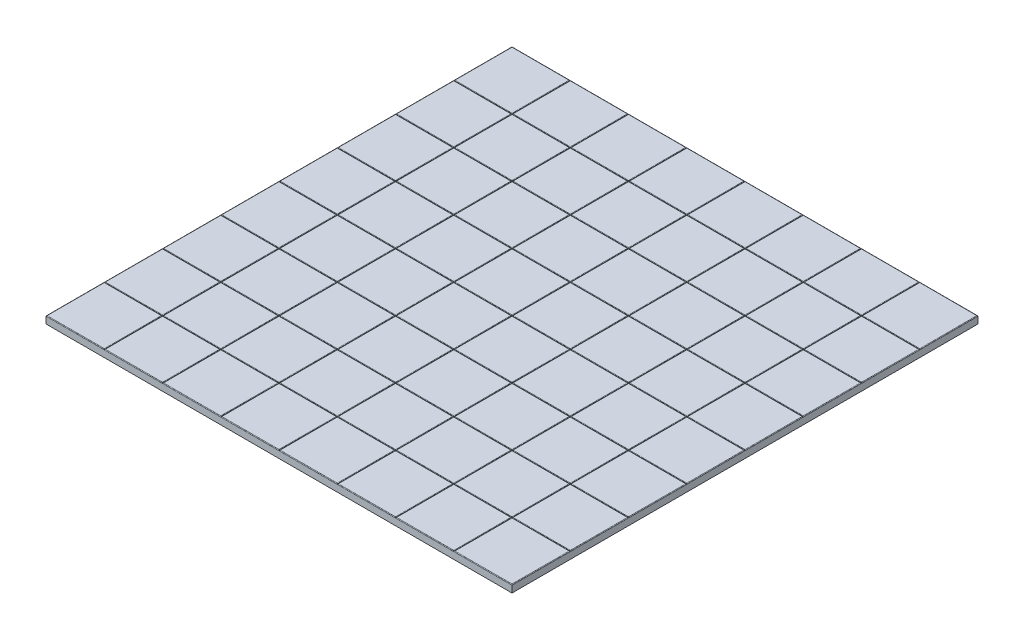
SolidWorks part; units mm, degrees
ref_plane "Front Plane" through (0, 0, 0) normal (0, 0, 1) x (1, 0, 0)
ref_plane "Top Plane" through (0, 0, 0) normal (0, 1, 0) x (1, 0, 0)
ref_plane "Right Plane" through (0, 0, 0) normal (1, 0, 0) x (0, 0, -1)
sketch "Sketch2" plane through (0, 0, 0) normal (0, 1, 0) x (1, 0, 0)
  line L1 (0, 0) -> (254, 0)
  line L2 (0, 0) -> (0, 254)
  line L3 (0, 254) -> (254, 254)
  line L4 (254, 0) -> (254, 254)
  dimension "D2" = 254
extrude "Boss-Extrude1" add sketch "Sketch2" against normal blind 3.9688
ref_plane "Plane1" through (0, 0, 3.175) normal (0, 0, 1) x (1, 0, 0)
ref_plane "Plane3" through (330.2, 0, 0) normal (1, 0, 0) x (0, 0, -1)
sketch "Sketch3" plane through (0, 0, 3.175) normal (0, 0, 1) x (1, 0, 0)
  line L0 (-0.3175, 0) -> (0.3175, 0)
  line L1 (31.4325, 0) -> (32.0675, 0)
  line L4 (63.1825, 0) -> (63.8175, 0)
  line L5 (94.9325, 0) -> (95.5675, 0)
  line L6 (126.6825, 0) -> (127.3175, 0)
  line L7 (158.4325, 0) -> (159.0675, 0)
  line L8 (190.1825, 0) -> (190.8175, 0)
  line L9 (221.9325, 0) -> (222.5675, 0)
  line L10 (253.6825, 0) -> (254.3175, 0)
  line L11 (285.4325, 0) -> (286.0675, 0)
  line L12 (317.1825, 0) -> (317.8175, 0)
  arc A0 (0.3175, 0) -> (0, -0.3175) centre (0.3175, -0.3175) ccw
  arc A1 (-0.3175, 0) -> (0, -0.3175) centre (-0.3175, -0.3175) cw
  arc A2 (32.0675, 0) -> (31.75, -0.3175) centre (32.0675, -0.3175) ccw
  arc A3 (31.4325, 0) -> (31.75, -0.3175) centre (31.4325, -0.3175) cw
  arc A4 (63.8175, 0) -> (63.5, -0.3175) centre (63.8175, -0.3175) ccw
  arc A5 (63.1825, 0) -> (63.5, -0.3175) centre (63.1825, -0.3175) cw
  arc A6 (95.5675, 0) -> (95.25, -0.3175) centre (95.5675, -0.3175) ccw
  arc A7 (94.9325, 0) -> (95.25, -0.3175) centre (94.9325, -0.3175) cw
  arc A8 (127.3175, 0) -> (127, -0.3175) centre (127.3175, -0.3175) ccw
  arc A9 (126.6825, 0) -> (127, -0.3175) centre (126.6825, -0.3175) cw
  arc A10 (159.0675, 0) -> (158.75, -0.3175) centre (159.0675, -0.3175) ccw
  arc A11 (158.4325, 0) -> (158.75, -0.3175) centre (158.4325, -0.3175) cw
  arc A12 (190.8175, 0) -> (190.5, -0.3175) centre (190.8175, -0.3175) ccw
  arc A13 (190.1825, 0) -> (190.5, -0.3175) centre (190.1825, -0.3175) cw
  arc A14 (222.5675, 0) -> (222.25, -0.3175) centre (222.5675, -0.3175) ccw
  arc A15 (221.9325, 0) -> (222.25, -0.3175) centre (221.9325, -0.3175) cw
  arc A16 (254.3175, 0) -> (254, -0.3175) centre (254.3175, -0.3175) ccw
  arc A17 (253.6825, 0) -> (254, -0.3175) centre (253.6825, -0.3175) cw
  arc A18 (286.0675, 0) -> (285.75, -0.3175) centre (286.0675, -0.3175) ccw
  arc A19 (285.4325, 0) -> (285.75, -0.3175) centre (285.4325, -0.3175) cw
  arc A20 (317.8175, 0) -> (317.5, -0.3175) centre (317.8175, -0.3175) ccw
  arc A21 (317.1825, 0) -> (317.5, -0.3175) centre (317.1825, -0.3175) cw
  dimension "D1" = 0.3175
extrude "Cut-Extrude2" cut sketch "Sketch3" against normal through all
sketch "Sketch4" plane through (330.2, 0, 0) normal (1, 0, 0) x (0, 0, -1)
  line L0 (31.4325, 0) -> (32.0675, 0)
  line L2 (-0.3175, 0) -> (0.3175, 0)
  line L4 (63.1825, 0) -> (63.8175, 0)
  line L5 (94.9325, 0) -> (95.5675, 0)
  line L6 (126.6825, 0) -> (127.3175, 0)
  line L7 (158.4325, 0) -> (159.0675, 0)
  line L8 (190.1825, 0) -> (190.8175, 0)
  line L9 (221.9325, 0) -> (222.5675, 0)
  line L10 (253.6825, 0) -> (254.3175, 0)
  line L11 (285.4325, 0) -> (286.0675, 0)
  line L12 (317.1825, 0) -> (317.8175, 0)
  arc A0 (0.3175, 0) -> (0, -0.3175) centre (0.3175, -0.3175) ccw
  arc A1 (-0.3175, 0) -> (0, -0.3175) centre (-0.3175, -0.3175) cw
  arc A2 (32.0675, 0) -> (31.75, -0.3175) centre (32.0675, -0.3175) ccw
  arc A3 (31.4325, 0) -> (31.75, -0.3175) centre (31.4325, -0.3175) cw
  arc A4 (63.8175, 0) -> (63.5, -0.3175) centre (63.8175, -0.3175) ccw
  arc A5 (63.1825, 0) -> (63.5, -0.3175) centre (63.1825, -0.3175) cw
  arc A6 (95.5675, 0) -> (95.25, -0.3175) centre (95.5675, -0.3175) ccw
  arc A7 (94.9325, 0) -> (95.25, -0.3175) centre (94.9325, -0.3175) cw
  arc A8 (127.3175, 0) -> (127, -0.3175) centre (127.3175, -0.3175) ccw
  arc A9 (126.6825, 0) -> (127, -0.3175) centre (126.6825, -0.3175) cw
  arc A10 (159.0675, 0) -> (158.75, -0.3175) centre (159.0675, -0.3175) ccw
  arc A11 (158.4325, 0) -> (158.75, -0.3175) centre (158.4325, -0.3175) cw
  arc A12 (190.8175, 0) -> (190.5, -0.3175) centre (190.8175, -0.3175) ccw
  arc A13 (190.1825, 0) -> (190.5, -0.3175) centre (190.1825, -0.3175) cw
  arc A14 (222.5675, 0) -> (222.25, -0.3175) centre (222.5675, -0.3175) ccw
  arc A15 (221.9325, 0) -> (222.25, -0.3175) centre (221.9325, -0.3175) cw
  arc A16 (254.3175, 0) -> (254, -0.3175) centre (254.3175, -0.3175) ccw
  arc A17 (253.6825, 0) -> (254, -0.3175) centre (253.6825, -0.3175) cw
  arc A18 (286.0675, 0) -> (285.75, -0.3175) centre (286.0675, -0.3175) ccw
  arc A19 (285.4325, 0) -> (285.75, -0.3175) centre (285.4325, -0.3175) cw
  arc A20 (317.8175, 0) -> (317.5, -0.3175) centre (317.8175, -0.3175) ccw
  arc A21 (317.1825, 0) -> (317.5, -0.3175) centre (317.1825, -0.3175) cw
  point P10 (0, 0)
  dimension "D1" = 0.3175
extrude "Cut-Extrude3" cut sketch "Sketch4" against normal through all
ref_point "Point2"
ref_point "Point4"
ref_point "Point6"
ref_point "Point8"
ref_point "Point10"
ref_point "Point12"
ref_point "Point14"
ref_point "Point18"
ref_point "Point20"
ref_point "Point22"
ref_point "Point24"
ref_point "Point26"
ref_point "Point28"
ref_point "Point30"
ref_point "Point32"
ref_point "Point34"
ref_point "Point36"
